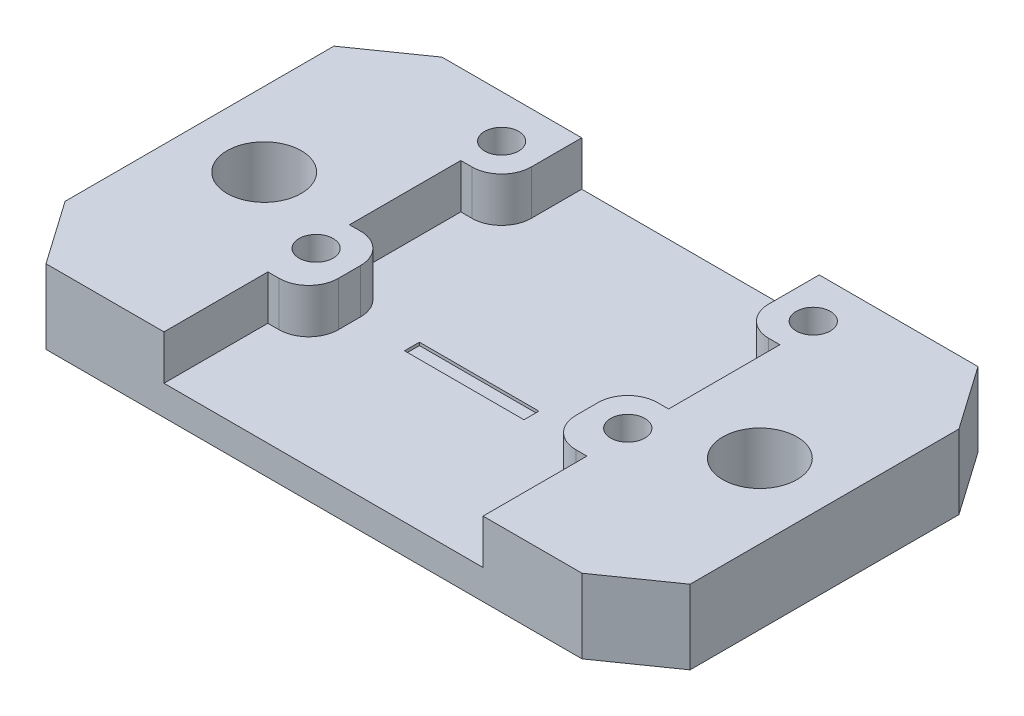
SolidWorks part; units mm, degrees
material "ABS"
ref_plane "Front Plane" through (0, 0, 0) normal (0, 0, 1) x (1, 0, 0)
ref_plane "Top Plane" through (0, 0, 0) normal (0, 1, 0) x (1, 0, 0)
ref_plane "Right Plane" through (0, 0, 0) normal (1, 0, 0) x (0, 0, -1)
sketch "Sketch2" plane through (0, 0, 0) normal (0, 1, 0) x (1, 0, 0)
  line L0 (0, 25.4) -> (10.2, 35.6)
  line L1 (0, 0) -> (25.4, 0)
  line L2 (0, 0) -> (0, 25.4)
  line L3 (0, 25.4) -> (25.4, 25.4)
  line L4 (25.4, 0) -> (25.4, 25.4)
  line L5 (25.4, 25.4) -> (15.2, 35.6)
  line L6 (10.2, 35.6) -> (15.2, 35.6)
  line L7 (35.6, 15.2) -> (35.6, 10.2)
  line L8 (25.4, 25.4) -> (35.6, 15.2)
  line L9 (25.4, 0) -> (35.6, 10.2)
  line L10 (15.2, -10.2) -> (10.2, -10.2)
  line L11 (25.4, 0) -> (15.2, -10.2)
  line L12 (0, 0) -> (10.2, -10.2)
  line L13 (-10.2, 10.2) -> (-10.2, 15.2)
  line L14 (0, 0) -> (-10.2, 10.2)
  line L15 (0, 25.4) -> (-10.2, 15.2)
  point P5 (12.7, 12.7)
  point P23 (12.7, 12.7)
  dimension "D1" = 25.4
  dimension "D2" = 25.4
  dimension "D3" = 45
  dimension "D4" = 5
  dimension "D5" = 45
  dimension "D6" = 4
extrude "Boss-Extrude6" add sketch "Sketch2" along normal blind 5 contours L1 L4 L3 L2
sketch "Sketch4" plane through (0, 0, 0) normal (0, -1, 0) x (1, 0, 0)
  line L0 (25.4, 0) -> (25.4, -25.4) construction
  line L1 (25.4, 0) -> (25.4, -9.7)
  line L2 (25.4, -15.7) -> (25.4, -25.4)
  line L3 (25.4, -25.4) -> (15.7, -25.4)
  line L4 (9.7, -25.4) -> (0, -25.4)
  line L5 (0, -25.4) -> (0, -15.7)
  line L6 (0, -9.7) -> (0, 0)
  line L7 (0, 0) -> (9.7, 0)
  line L8 (15.7, 0) -> (25.4, 0)
  line L9 (9.7, 0) -> (15.7, 0)
  arc A0 (25.4, -15.7) -> (25.4, -9.7) centre (29.4, -12.7) ccw
  arc A1 (9.7, -25.4) -> (15.7, -25.4) centre (12.7, -29.4) ccw
  arc A2 (0, -9.7) -> (0, -15.7) centre (-4, -12.7) ccw
  arc A4 (15.7, 0) -> (9.7, 0) centre (12.7, 4) ccw [skipped]
  point P1 (12.7, -12.7)
  point P28 (12.7, -12.7)
  dimension "D1" = 10
  dimension "D2" = 4
  dimension "D3" = 4
extrude "Boss-Extrude7" add sketch "Sketch4" against normal blind 5
fillet "Fillet1" radius 5 6 edges at (25.4, 2.5, -15.7) (25.4, 2.5, -9.7) (0, 2.5, -9.7) (0, 2.5, -15.7) (9.7, 2.5, -25.4) (15.7, 2.5, -25.4)
sketch "Sketch5" plane through (0, 5, 0) normal (0, 1, 0) x (1, 0, 0)
  circle A0 centre (-4, 12.7) radius 1
  circle A1 centre (12.7, 29.4) radius 1
  circle A2 centre (29.4, 12.7) radius 1
  circle A3 centre (12.7, -4) radius 1 [skipped]
  point P3 (12.7, 12.7)
  point P13 (12.7, 12.7)
  dimension "D1" = 2
  dimension "D2" = 4
extrude "Cut-Extrude1" cut sketch "Sketch5" against normal blind 5
sketch "Sketch6" plane through (0, 5, 0) normal (0, 1, 0) x (1, 0, 0)
  line L1 (0, 25.4) -> (28.0983, 25.4)
  line L2 (0, 25.4) -> (0, 35.2018)
  line L3 (0, 35.2018) -> (28.0983, 35.2018)
  line L4 (28.0983, 25.4) -> (28.0983, 35.2018)
extrude "Cut-Extrude2" cut sketch "Sketch6" against normal through all
sketch "Sketch7" plane through (0, 5, 0) normal (0, 1, 0) x (1, 0, 0)
  line L1 (-9, 25.4) -> (34.4, 25.4)
  line L2 (-9, 25.4) -> (-9, 0)
  line L3 (-9, 0) -> (34.4, 0)
  line L4 (34.4, 25.4) -> (34.4, 0)
  arc A0 (-4.5, 17.6749) -> (-4.5, 7.7251) centre (-4, 12.7) ccw construction
  arc A1 (29.9, 7.7251) -> (29.9, 17.6749) centre (29.4, 12.7) ccw construction
  circle A2 centre (-4, 12.7) radius 2.5
  circle A3 centre (29.4, 12.7) radius 2.5
  dimension "D1" = 5
  dimension "D2" = 5
extrude "Boss-Extrude8" add sketch "Sketch7" against normal up to surface (5 mm away) up to face at (-4, 0, -11.7)
sketch "Sketch8" plane through (0, 5, 0) normal (0, 1, 0) x (1, 0, 0)
  circle A0 centre (-4, 12.7) radius 2.5
  circle A1 centre (29.4, 12.7) radius 2.5
  dimension "D1" = 5
  dimension "D2" = 5
extrude "Cut-Extrude3" cut sketch "Sketch8" against normal blind 10
sketch "Sketch9" plane through (0, 5, 0) normal (0, 1, 0) x (1, 0, 0)
  line L0 (12.7, 25.4) -> (12.7, 17.3168) construction
  line L1 (-9, 25.4) -> (34.4, 25.4) construction
  line L2 (-9, 0) -> (34.4, 0) construction
  line L3 (26.2, 20) -> (20.7, 20)
  line L4 (-0.8, 25.5) -> (4.7, 25.5)
  line L5 (-0.8, 25.5) -> (-0.8, 20)
  line L6 (-0.8, 20) -> (4.7, 20)
  line L7 (4.7, 25.5) -> (4.7, 20)
  line L8 (20.7, 25.5) -> (20.7, 20)
  line L9 (26.2, 25.5) -> (20.7, 25.5)
  line L10 (26.2, 25.5) -> (26.2, 20)
  line L11 (-0.8, 12.5) -> (-0.8, 7)
  line L12 (-0.8, 12.5) -> (4.7, 12.5)
  line L13 (4.7, 12.5) -> (4.7, 7)
  line L14 (-0.8, 7) -> (4.7, 7)
  line L15 (26.2, 7) -> (20.7, 7)
  line L16 (20.7, 12.5) -> (20.7, 7)
  line L17 (26.2, 12.5) -> (20.7, 12.5)
  line L18 (26.2, 12.5) -> (26.2, 7)
  line L19 (1.95, 7) -> (1.95, 0)
  line L21 (4.7, 25.5) -> (20.7, 25.5)
  line L23 (1.95, 0) -> (23.45, 0)
  line L24 (23.45, 0) -> (23.45, 7)
  line L25 (1.95, 20) -> (1.95, 12.5)
  line L26 (23.45, 20) -> (23.45, 12.5)
  circle A0 centre (2.2, 10) radius 1.15
  circle A1 centre (23.2, 10) radius 1.15
  circle A2 centre (2.2, 22.5) radius 1.15
  circle A3 centre (23.2, 22.5) radius 1.15
  dimension "D1" = 2.3
  dimension "D2" = 10
  dimension "D3" = 10.5
  dimension "D6" = 3
  dimension "D8" = 2.5
  dimension "D10" = 21
  dimension "D5" = 3
  dimension "D7" = 2.5
  dimension "D4" = 2
  dimension "D9" = 2
extrude "Cut-Extrude4" cut sketch "Sketch9" against normal blind 3
fillet "Fillet2" radius 2 6 edges at (20.7, 3.5, -12.5) (20.7, 3.5, -7) (20.7, 3.5, -20) (4.7, 3.5, -20) (4.7, 3.5, -12.5) (4.7, 3.5, -7)
chamfer "Chamfer1" distance 3 angle 55 4 edges at (34.4, 2.5, -25.4) (34.4, 2.5, 0) (-9, 2.5, 0) (-9, 2.5, -25.4)
sketch "Sketch10" plane through (0, 2, 0) normal (0, 1, 0) x (1, 0, 0)
  line L0 (8.1563, 10) -> (16.2061, 10)
  line L1 (8.1563, 10) -> (8.1563, 11.0054)
  line L2 (8.1563, 11.0054) -> (16.2061, 11.0054)
  line L3 (16.2061, 11.0054) -> (16.2061, 10)
extrude "Cut-Extrude5" cut sketch "Sketch10" against normal blind 0.2
